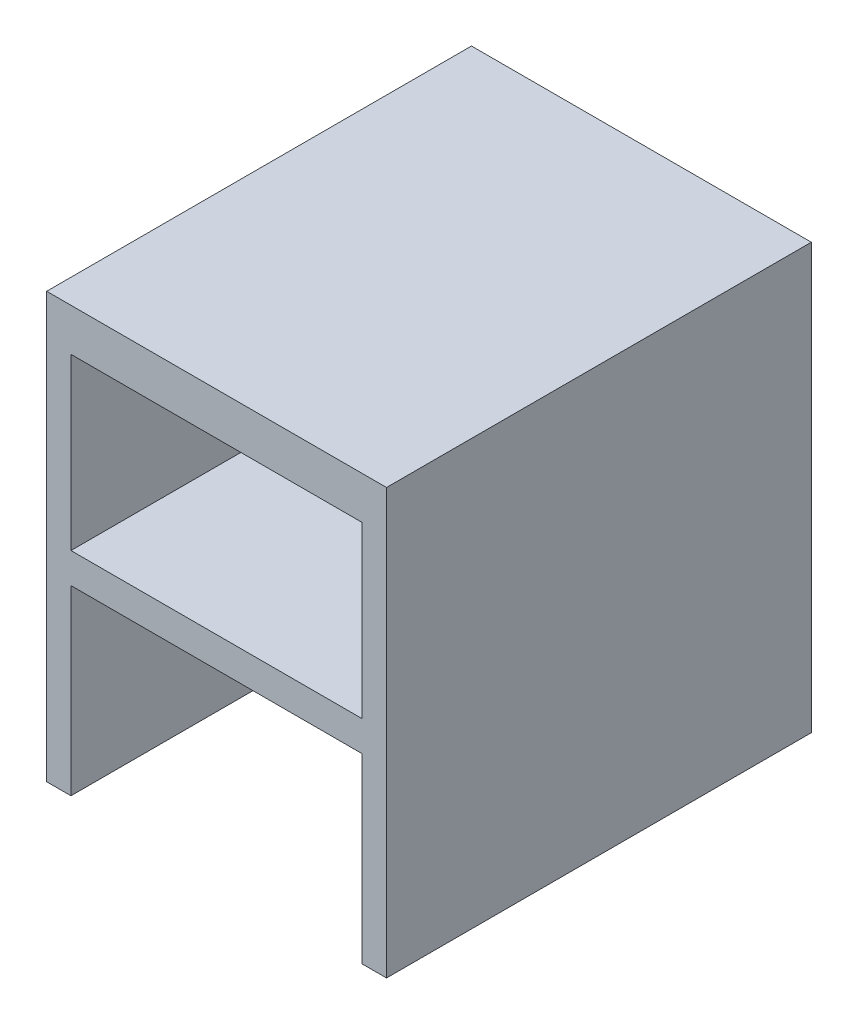
SolidWorks part; units mm, degrees
ref_plane "Front" through (0, 0, 0) normal (0, 0, 1) x (1, 0, 0)
ref_plane "Top" through (0, 0, 0) normal (0, 1, 0) x (1, 0, 0)
ref_plane "Right" through (0, 0, 0) normal (1, 0, 0) x (0, 0, -1)
sketch "Sketch1" plane through (0, 0, 0) normal (0, 0, 1) x (1, 0, 0)
  line L0 (0, 0) -> (0, 70)
  line L1 (0, 70) -> (56, 70)
  line L2 (56, 70) -> (56, 0)
  line L3 (56, 0) -> (52, 0)
  line L4 (52, 0) -> (52, 63)
  line L5 (52, 63) -> (4, 63)
  line L6 (4, 63) -> (4, 0)
  line L7 (4, 0) -> (0, 0)
  line L9 (4, 35) -> (52, 35)
  line L10 (4, 35) -> (4, 30)
  line L11 (4, 30) -> (52, 30)
  line L12 (52, 35) -> (52, 30)
  dimension "D1" = 48
  dimension "D2" = 4
  dimension "D3" = 4
  dimension "D4" = 7
  dimension "D5" = 70
  dimension "D6" = 5
  dimension "D7" = 40
extrude "Boss-Extrude1" add sketch "Sketch1" along normal blind 70 contours L7 L6 L5 L4 L3 L2 L1 L0 | L9 L12 L11 L10
